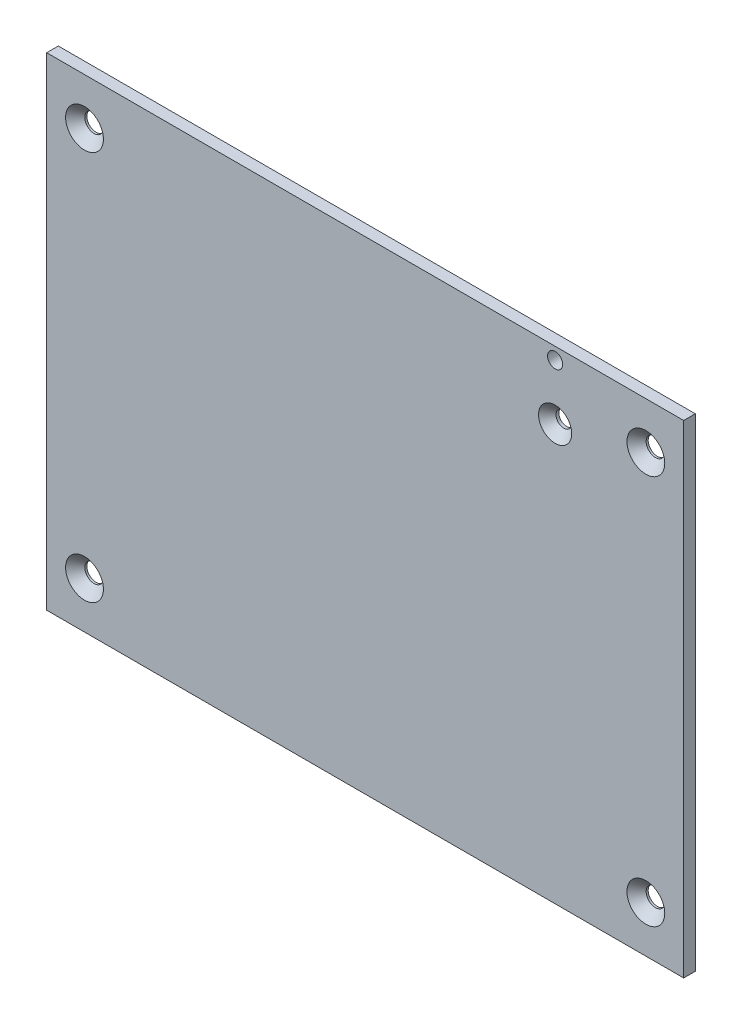
SolidWorks part; units mm, degrees
ref_plane "Front Plane" through (0, 0, 0) normal (0, 0, 1) x (1, 0, 0)
ref_plane "Top Plane" through (0, 0, 0) normal (0, 1, 0) x (1, 0, 0)
ref_plane "Right Plane" through (0, 0, 0) normal (1, 0, 0) x (0, 0, -1)
sketch "Sketch1" plane through (0, 0, 0) normal (0, 0, 1) x (1, 0, 0)
  line L0 (55.75, -83) -> (-55.75, -83) construction
  line L1 (-54.75, 0) -> (54.75, 0)
  line L2 (-54.75, 0) -> (-54.75, -83)
  line L3 (-54.75, -83) -> (54.75, -83)
  line L4 (54.75, 0) -> (54.75, -83)
  line L5 (52.75, 0) -> (52.75, -83) construction
  dimension "D1" = 2
extrude "Boss-Extrude1" add sketch "Sketch1" along normal blind 2
hole_wizard "CSK for M3 Flat Countersunk Head Screw1" positions "Sketch4" profile "Sketch3" countersink size "M3" standard "JIS" end condition up to next
sketch "Sketch4" plane through (0, 0, 2) normal (0, 0, 1) x (1, 0, 0)
  line L0 (-54.75, 0) -> (-54.75, -83) construction
  line L1 (54.75, 0) -> (-54.75, 0) construction
  line L2 (-54.75, -83) -> (54.75, -83) construction
  line L3 (54.75, -83) -> (54.75, 0) construction
  point P0 (-48.25, -8)
  point P1 (-48.25, -75)
  point P3 (48.25, -75)
  point P5 (48.25, -8)
  dimension "D1" = 6.5
  dimension "D2" = 8
  dimension "D3" = 6.5
  dimension "D4" = 8
  dimension "D5" = 8
  dimension "D6" = 6.5
  dimension "D7" = 6.5
  dimension "D8" = 8
sketch "Sketch3" plane through (-48.25, -8, 2) normal (1, 0, 0) x (0, -1, 0)
  line L0 (0, 0) -> (0, 2)
  line L1 (0, 2) -> (1.6, 2)
  line L2 (1.6, 2) -> (1.6, 1.65)
  line L3 (1.6, 1.65) -> (3.25, 0)
  line L5 (3.25, 0) -> (0, 0)
  line L6 (-1.6, 1.65) -> (-3.25, 0) construction
  line L11 (0, -6.35) -> (0, 107.95) construction
  dimension "Thru Hole Dia." = 3.2
  dimension "Thru Hole Depth" = 2
  dimension "Near C'Sink Dia." = 6.5
  dimension "Near C'Sink Angle" = 90
hole_wizard "CSK for M2.5 Flat Countersunk Head Screw1" positions "Sketch6" profile "Sketch5" countersink size "M2.5" standard "JIS" end condition up to next
sketch "Sketch6" plane through (0, 0, 2) normal (0, 0, 1) x (1, 0, 0)
  line L4 (54.75, 0) -> (-54.75, 0) construction
  line L5 (54.75, -83) -> (54.75, 0) construction
  point P0 (32.65, -11.6)
  dimension "D1" = 11.6
  dimension "D2" = 22.1
sketch "Sketch5" plane through (32.65, -11.6, 2) normal (1, 0, 0) x (0, -1, 0)
  line L0 (0, 0) -> (0, 2)
  line L1 (0, 2) -> (1.35, 2)
  line L2 (1.35, 2) -> (1.35, 1.5)
  line L3 (1.35, 1.5) -> (2.85, 0)
  line L5 (2.85, 0) -> (0, 0)
  line L6 (-1.35, 1.5) -> (-2.85, 0) construction
  line L11 (0, -6.35) -> (0, 107.95) construction
  dimension "Thru Hole Dia." = 2.7
  dimension "Thru Hole Depth" = 2
  dimension "Near C'Sink Dia." = 5.7
  dimension "Near C'Sink Angle" = 90
hole_wizard "Ø2.6 (2.6) Diameter Hole1" positions "Sketch8" profile "Sketch7" hole size "Ø2.6" standard "Ansi Metric" end condition up to next
sketch "Sketch8" plane through (0, 0, 2) normal (0, 0, 1) x (1, 0, 0)
  line L1 (54.75, -83) -> (54.75, 0) construction
  circle A0 centre (32.65, -11.6) radius 1.35 construction
  point P0 (32.65, -2.07)
  dimension "D2" = 9.53
  dimension "D1" = 22.1
sketch "Sketch7" plane through (32.65, -2.07, 2) normal (1, 0, 0) x (0, -1, 0)
  line L0 (0, 0) -> (0, 2)
  line L1 (0, 2) -> (1.3, 2)
  line L2 (1.3, 2) -> (1.3, 0)
  line L5 (1.3, 0) -> (0, 0)
  line L11 (0, -6.35) -> (0, 107.95) construction
  dimension "Thru Hole Dia." = 2.6
  dimension "Thru Hole Depth" = 2
